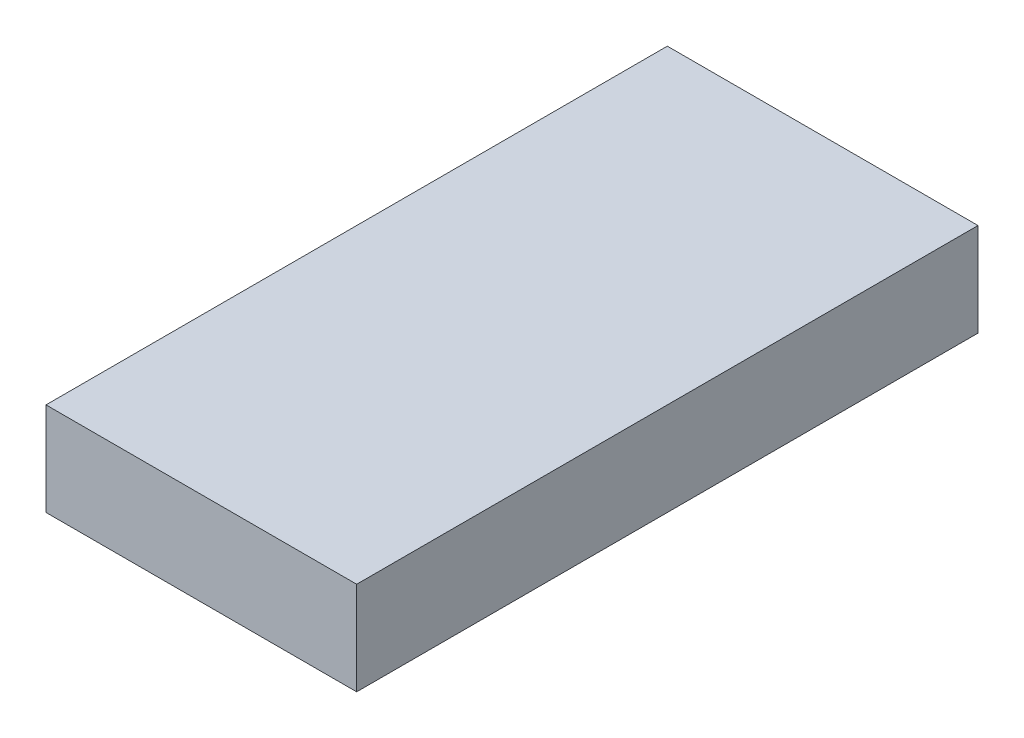
SolidWorks part; units mm, degrees
ref_plane "Front" through (0, 0, 0) normal (0, 0, 1) x (1, 0, 0)
ref_plane "Top" through (0, 0, 0) normal (0, 1, 0) x (1, 0, 0)
ref_plane "Right" through (0, 0, 0) normal (1, 0, 0) x (0, 0, -1)
sketch "Sketch1" plane through (0, 0, 0) normal (0, 1, 0) x (1, 0, 0)
  line L1 (0, 0) -> (-5, 0)
  line L2 (0, 0) -> (0, 10)
  line L3 (0, 10) -> (-5, 10)
  line L4 (-5, 0) -> (-5, 10)
  dimension "D1" = 10
  dimension "D2" = 5
extrude "Boss-Extrude1" add sketch "Sketch1" along normal blind 1.5
